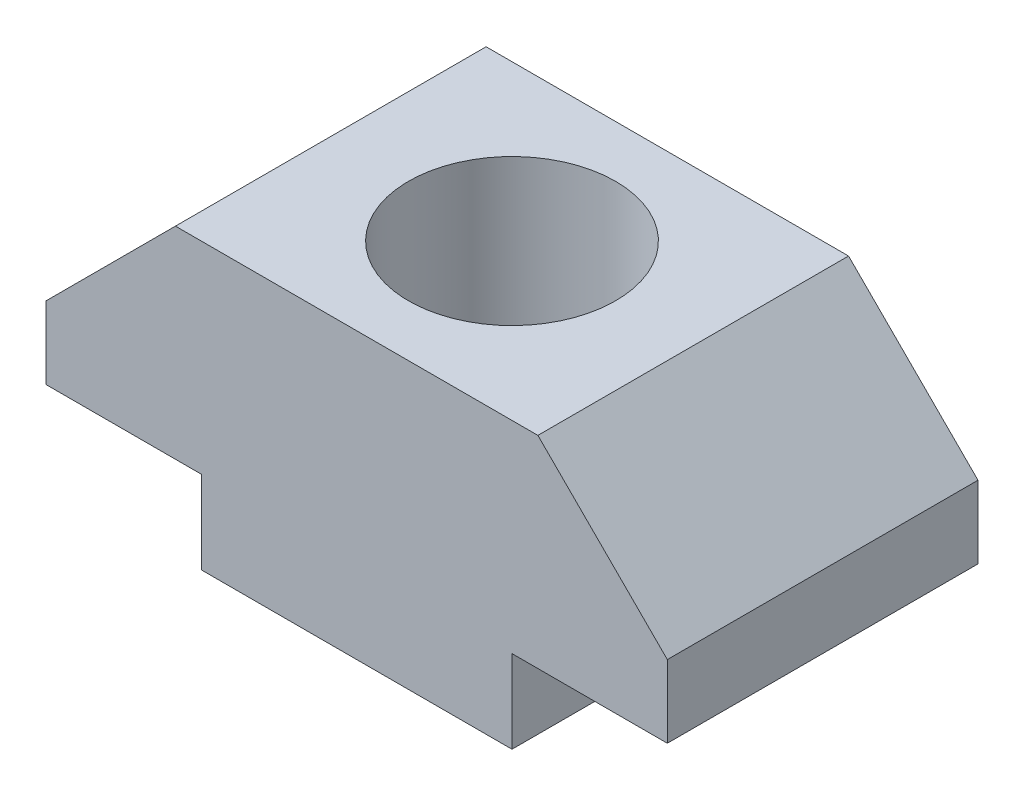
SolidWorks part; units mm, degrees
ref_plane "Front Plane" through (0, 0, 0) normal (0, 0, 1) x (1, 0, 0)
ref_plane "Top Plane" through (0, 0, 0) normal (0, 1, 0) x (1, 0, 0)
ref_plane "Right Plane" through (0, 0, 0) normal (1, 0, 0) x (0, 0, -1)
sketch "Sketch1" plane through (0, 0, 0) normal (0, 0, 1) x (1, 0, 0)
  line L0 (-3, 0) -> (3, 0)
  line L1 (0, 9.6092) -> (0, -4.7207) construction
  line L2 (3, 0) -> (3, 1.6)
  line L3 (3, 1.6) -> (6, 1.6)
  line L4 (6, 1.6) -> (6, 3)
  line L5 (6, 3) -> (3.5, 5.5)
  line L6 (3.5, 5.5) -> (-3.5, 5.5)
  line L8 (-3.5, 5.5) -> (-6, 3)
  line L9 (-6, 3) -> (-6, 1.6)
  line L10 (-6, 1.6) -> (-3, 1.6)
  line L11 (-3, 1.6) -> (-3, 0)
  dimension "D1" = 1.6
  dimension "D2" = 6
  dimension "D3" = 5.5
  dimension "D4" = 12
  dimension "D5" = 135
  dimension "D6" = 7
extrude "Extrude1" add sketch "Sketch1" along normal mid plane 6
sketch "Sketch2" plane through (0, 0, 0) normal (0, 1, 0) x (1, 0, 0)
  circle A0 centre (0, 0) radius 2
  dimension "D1" = 4
extrude "Cut-Extrude1" cut sketch "Sketch2" along normal up to next
cosmetic thread "Cosmetic Thread1"
